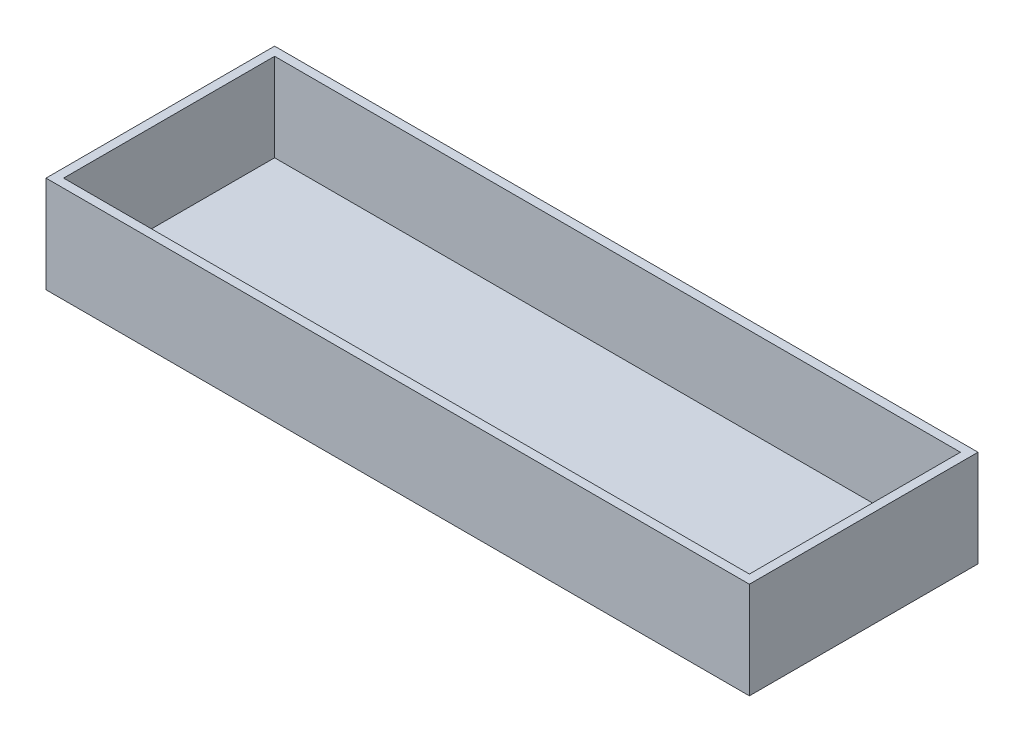
SolidWorks part; units mm, degrees
ref_plane "Front Plane" through (0, 0, 0) normal (0, 0, 1) x (1, 0, 0)
ref_plane "Top Plane" through (0, 0, 0) normal (0, 1, 0) x (1, 0, 0)
ref_plane "Right Plane" through (0, 0, 0) normal (1, 0, 0) x (0, 0, -1)
sketch "Sketch1" plane through (0, 0, 0) normal (0, 1, 0) x (1, 0, 0)
  line L1 (0, 0) -> (160, 0)
  line L2 (0, 0) -> (0, 52)
  line L3 (0, 52) -> (160, 52)
  line L4 (160, 0) -> (160, 52)
extrude "Boss-Extrude1" add sketch "Sketch1" along normal blind 22 contours L2 L1 L4 L3
shell "Shell1" thickness 2
